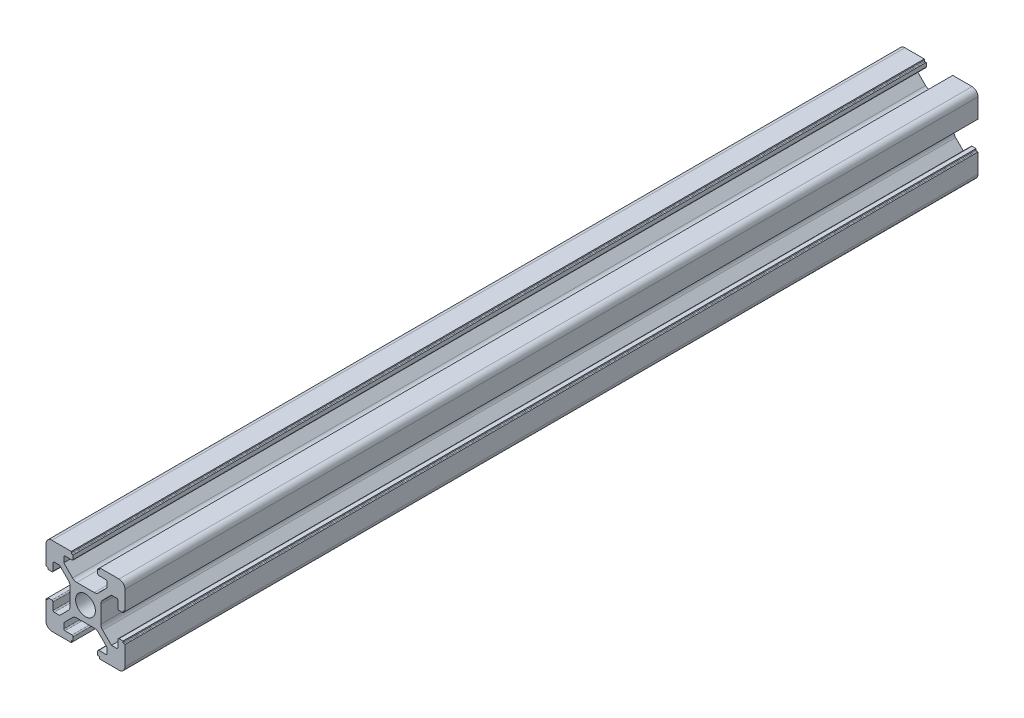
SolidWorks part; units mm, degrees
ref_plane "前视基准面" through (0, 0, 0) normal (0, 0, 1) x (1, 0, 0)
ref_plane "上视基准面" through (0, 0, 0) normal (0, 1, 0) x (1, 0, 0)
ref_plane "右视基准面" through (0, 0, 0) normal (1, 0, 0) x (0, 0, -1)
sketch "草图1" plane through (0, 0, 0) normal (0, 0, 1) x (1, 0, 0)
  line L0 (4.216, 3.2442) -> (6.4367, 5.4649)
  line L1 (6.4367, 5.4649) -> (7.7767, 5.4649)
  line L2 (8.0767, 5.1649) -> (8.0767, 3.3649)
  line L3 (8.3767, 3.0649) -> (9.3767, 3.0649)
  line L4 (9.3767, 3.0649) -> (9.3767, 3.3649)
  line L5 (9.5767, 3.5649) -> (9.8767, 3.5649)
  line L6 (9.8767, 3.5649) -> (9.8767, 8.4649)
  line L7 (8.3767, 9.9649) -> (3.4767, 9.9649)
  line L8 (3.4767, 9.9649) -> (3.4767, 9.6649)
  line L9 (3.2767, 9.4649) -> (2.9767, 9.4649)
  line L10 (2.9767, 9.4649) -> (2.9767, 8.4649)
  line L11 (3.2767, 8.1649) -> (5.0767, 8.1649)
  line L12 (5.3767, 7.8649) -> (5.3767, 6.5249)
  line L13 (5.3767, 6.5249) -> (3.156, 4.3042)
  line L14 (2.0953, 3.8649) -> (-2.342, 3.8649)
  line L15 (-3.4027, 4.3042) -> (-5.6233, 6.5249)
  line L16 (-5.6233, 6.5249) -> (-5.6233, 7.8649)
  line L17 (-5.3233, 8.1649) -> (-3.5233, 8.1649)
  line L18 (-3.2233, 8.4649) -> (-3.2233, 9.4649)
  line L19 (-3.2233, 9.4649) -> (-3.5233, 9.4649)
  line L20 (-3.7233, 9.6649) -> (-3.7233, 9.9649)
  line L21 (-3.7233, 9.9649) -> (-8.6233, 9.9649)
  line L22 (-10.1233, 8.4649) -> (-10.1233, 3.5649)
  line L23 (-10.1233, 3.5649) -> (-9.8233, 3.5649)
  line L24 (-9.6233, 3.3649) -> (-9.6233, 3.0649)
  line L25 (-9.6233, 3.0649) -> (-8.6233, 3.0649)
  line L26 (-8.3233, 3.3649) -> (-8.3233, 5.1649)
  line L27 (-8.0233, 5.4649) -> (-6.6833, 5.4649)
  line L28 (-6.6833, 5.4649) -> (-4.4627, 3.2442)
  line L29 (-4.0233, 2.1836) -> (-4.0233, -2.2538)
  line L30 (-4.4627, -3.3144) -> (-6.6833, -5.5351)
  line L31 (-6.6833, -5.5351) -> (-8.0233, -5.5351)
  line L32 (-8.3233, -5.2351) -> (-8.3233, -3.4351)
  line L33 (-8.6233, -3.1351) -> (-9.6233, -3.1351)
  line L34 (-9.6233, -3.1351) -> (-9.6233, -3.4351)
  line L35 (-9.8233, -3.6351) -> (-10.1233, -3.6351)
  line L36 (-10.1233, -3.6351) -> (-10.1233, -8.5351)
  line L37 (-8.6233, -10.0351) -> (-3.7233, -10.0351)
  line L38 (-3.7233, -10.0351) -> (-3.7233, -9.7351)
  line L39 (-3.5233, -9.5351) -> (-3.2233, -9.5351)
  line L40 (-3.2233, -9.5351) -> (-3.2233, -8.5351)
  line L41 (-3.5233, -8.2351) -> (-5.3233, -8.2351)
  line L42 (-5.6233, -7.9351) -> (-5.6233, -6.5951)
  line L43 (-5.6233, -6.5951) -> (-3.4027, -4.3744)
  line L44 (-2.342, -3.9351) -> (2.0953, -3.9351)
  line L45 (3.156, -4.3744) -> (5.3767, -6.5951)
  line L46 (5.3767, -6.5951) -> (5.3767, -7.9351)
  line L47 (5.0767, -8.2351) -> (3.2767, -8.2351)
  line L48 (2.9767, -8.5351) -> (2.9767, -9.5351)
  line L49 (2.9767, -9.5351) -> (3.2767, -9.5351)
  line L50 (3.4767, -9.7351) -> (3.4767, -10.0351)
  line L51 (3.4767, -10.0351) -> (8.3767, -10.0351)
  line L52 (9.8767, -8.5351) -> (9.8767, -3.6351)
  line L53 (9.8767, -3.6351) -> (9.5767, -3.6351)
  line L54 (9.3767, -3.4351) -> (9.3767, -3.1351)
  line L55 (9.3767, -3.1351) -> (8.3767, -3.1351)
  line L56 (8.0767, -3.4351) -> (8.0767, -5.2351)
  line L57 (7.7767, -5.5351) -> (6.4367, -5.5351)
  line L58 (6.4367, -5.5351) -> (4.216, -3.3144)
  line L59 (3.7767, -2.2538) -> (3.7767, 2.1836)
  circle A0 centre (-0.1233, -0.0351) radius 2.5
  arc A1 (8.0767, 5.1649) -> (7.7767, 5.4649) centre (7.7767, 5.1649) ccw
  arc A2 (8.0767, 3.3649) -> (8.3767, 3.0649) centre (8.3767, 3.3649) ccw
  arc A3 (9.5767, 3.5649) -> (9.3767, 3.3649) centre (9.5767, 3.3649) ccw
  arc A4 (9.8767, 8.4649) -> (8.3767, 9.9649) centre (8.3767, 8.4649) ccw
  arc A5 (3.2767, 9.4649) -> (3.4767, 9.6649) centre (3.2767, 9.6649) ccw
  arc A6 (2.9767, 8.4649) -> (3.2767, 8.1649) centre (3.2767, 8.4649) ccw
  arc A7 (5.3767, 7.8649) -> (5.0767, 8.1649) centre (5.0767, 7.8649) ccw
  arc A8 (2.0953, 3.8649) -> (3.156, 4.3042) centre (2.0953, 5.3649) ccw
  arc A9 (-3.4027, 4.3042) -> (-2.342, 3.8649) centre (-2.342, 5.3649) ccw
  arc A10 (-5.3233, 8.1649) -> (-5.6233, 7.8649) centre (-5.3233, 7.8649) ccw
  arc A11 (-3.5233, 8.1649) -> (-3.2233, 8.4649) centre (-3.5233, 8.4649) ccw
  arc A12 (-3.7233, 9.6649) -> (-3.5233, 9.4649) centre (-3.5233, 9.6649) ccw
  arc A13 (-8.6233, 9.9649) -> (-10.1233, 8.4649) centre (-8.6233, 8.4649) ccw
  arc A14 (-9.6233, 3.3649) -> (-9.8233, 3.5649) centre (-9.8233, 3.3649) ccw
  arc A15 (-8.6233, 3.0649) -> (-8.3233, 3.3649) centre (-8.6233, 3.3649) ccw
  arc A16 (-8.0233, 5.4649) -> (-8.3233, 5.1649) centre (-8.0233, 5.1649) ccw
  arc A17 (-4.0233, 2.1836) -> (-4.4627, 3.2442) centre (-5.5233, 2.1836) ccw
  arc A18 (-4.4627, -3.3144) -> (-4.0233, -2.2538) centre (-5.5233, -2.2538) ccw
  arc A19 (-8.3233, -5.2351) -> (-8.0233, -5.5351) centre (-8.0233, -5.2351) ccw
  arc A20 (-8.3233, -3.4351) -> (-8.6233, -3.1351) centre (-8.6233, -3.4351) ccw
  arc A21 (-9.8233, -3.6351) -> (-9.6233, -3.4351) centre (-9.8233, -3.4351) ccw
  arc A22 (-10.1233, -8.5351) -> (-8.6233, -10.0351) centre (-8.6233, -8.5351) ccw
  arc A23 (-3.5233, -9.5351) -> (-3.7233, -9.7351) centre (-3.5233, -9.7351) ccw
  arc A24 (-3.2233, -8.5351) -> (-3.5233, -8.2351) centre (-3.5233, -8.5351) ccw
  arc A25 (-5.6233, -7.9351) -> (-5.3233, -8.2351) centre (-5.3233, -7.9351) ccw
  arc A26 (-2.342, -3.9351) -> (-3.4027, -4.3744) centre (-2.342, -5.4351) ccw
  arc A27 (3.156, -4.3744) -> (2.0953, -3.9351) centre (2.0953, -5.4351) ccw
  arc A28 (5.0767, -8.2351) -> (5.3767, -7.9351) centre (5.0767, -7.9351) ccw
  arc A29 (3.2767, -8.2351) -> (2.9767, -8.5351) centre (3.2767, -8.5351) ccw
  arc A30 (3.4767, -9.7351) -> (3.2767, -9.5351) centre (3.2767, -9.7351) ccw
  arc A31 (8.3767, -10.0351) -> (9.8767, -8.5351) centre (8.3767, -8.5351) ccw
  arc A32 (9.3767, -3.4351) -> (9.5767, -3.6351) centre (9.5767, -3.4351) ccw
  arc A33 (8.3767, -3.1351) -> (8.0767, -3.4351) centre (8.3767, -3.4351) ccw
  arc A34 (7.7767, -5.5351) -> (8.0767, -5.2351) centre (7.7767, -5.2351) ccw
  arc A35 (3.7767, -2.2538) -> (4.216, -3.3144) centre (5.2767, -2.2538) ccw
  arc A36 (4.216, 3.2442) -> (3.7767, 2.1836) centre (5.2767, 2.1836) ccw
extrude "凸台-拉伸1" add sketch "草图1" along normal blind 216
